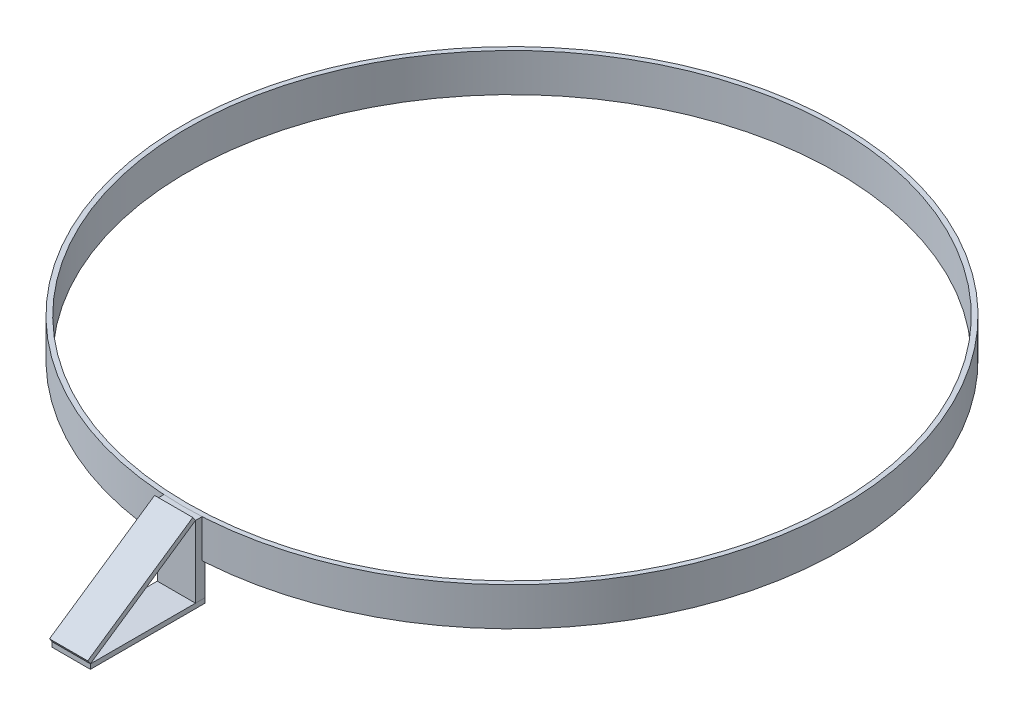
SolidWorks part; units mm, degrees
ref_plane "Front Plane" through (0, 0, 0) normal (0, 0, 1) x (1, 0, 0)
ref_plane "Top Plane" through (0, 0, 0) normal (0, 1, 0) x (1, 0, 0)
ref_plane "Right Plane" through (0, 0, 0) normal (1, 0, 0) x (0, 0, -1)
sketch "Sketch1" plane through (0, 0, 0) normal (0, 1, 0) x (1, 0, 0)
  circle A0 centre (0, 0) radius 219.075
extrude "Boss-Extrude1" add sketch "Sketch1" along normal blind 25.4
sketch "Sketch2" plane through (0, 25.4, 0) normal (0, 1, 0) x (1, 0, 0)
  circle A0 centre (0, 0) radius 215.9
  point P3 (0, 0)
extrude "Cut-Extrude1" cut sketch "Sketch2" against normal through all contours A0
ref_plane "Plane2" through (0, -25.4, 0) normal (0, 1, 0) x (1, 0, 0)
sketch "Sketch7" plane through (0, -25.4, 0) normal (0, 1, 0) x (1, 0, 0)
  line L0 (0, -27.94) -> (0, 27.94) construction
  line L1 (-12.7, -216.7564) -> (12.7, -216.7564)
  line L2 (-12.7, -216.7564) -> (-12.7, -223.1064)
  line L3 (-12.7, -223.1064) -> (12.7, -223.1064)
  line L4 (12.7, -216.7564) -> (12.7, -223.1064)
  line L5 (-12.7, -216.7564) -> (12.7, -223.1064) construction
  line L6 (-12.7, -223.1064) -> (12.7, -216.7564) construction
  point P0 (0, -219.9314)
  point P7 (0, 0)
  point P8 (0, 0)
  point P9 (0, -222.3976)
  point P10 (0, -217.288)
  point P11 (0, 0)
  point P12 (0, -219.1746)
  point P13 (0, -219.9314)
extrude "Boss-Extrude7" add sketch "Sketch7" along normal blind 50.8 separate body contours L1 L4 L3 L2
ref_plane "Plane6" through (0, -25.4, 0) normal (0, 1, 0) x (1, 0, 0)
sketch "Sketch13" plane through (0, -25.4, 0) normal (0, 1, 0) x (1, 0, 0)
  line L1 (-12.7, -216.7564) -> (12.7, -216.7564)
  line L2 (-12.7, -216.7564) -> (-12.7, -292.9564)
  line L3 (-12.7, -292.9564) -> (12.7, -292.9564)
  line L4 (12.7, -216.7564) -> (12.7, -292.9564)
  line L5 (12.7, -216.7564) -> (12.7, -223.1064) construction
  point P4 (0, 0)
  point P5 (0, 0)
  point P6 (0, 0)
  point P7 (-12.6997, -215.5262)
  point P8 (0, 0)
  point P9 (0, 0)
  point P10 (0, 0)
  point P11 (0, 0)
  point P12 (0, 0)
  point P13 (-12.7, -215.5262)
  point P14 (-12.7, -216.7564)
  point P16 (0, 0)
  point P17 (12.7, -216.7564)
extrude "Boss-Extrude11" add sketch "Sketch13" along normal blind 3.175 separate body contours L2 L3 L4 L1
sketch "Sketch19" plane through (0, -22.225, 0) normal (0, 1, 0) x (1, 0, 0)
  line L0 (12.7, -223.1064) -> (-12.7, -223.1064)
  line L1 (12.7, -223.1064) -> (-12.7, -223.1064)
sketch "Sketch21" plane through (12.7, 0, 0) normal (1, 0, 0) x (0, 0, -1)
  line L0 (-223.1064, 25.4) -> (-292.9564, -22.225)
ref_plane "Plane9" through (0, 121.1829, 82.6247) normal (0, 0.8262, 0.5633) x (0, -0.5633, 0.8262)
sketch "Sketch22" plane through (0, 121.1829, 82.6247) normal (0, 0.8262, 0.5633) x (0, -0.5633, 0.8262)
  line L1 (170.0278, 12.7) -> (254.5687, 12.7)
  line L2 (170.0278, 12.7) -> (170.0278, -12.7)
  line L3 (170.0278, -12.7) -> (254.5687, -12.7)
  line L4 (254.5687, 12.7) -> (254.5687, -12.7)
extrude "Boss-Extrude12" add sketch "Sketch22" along normal blind 3.175 separate body
